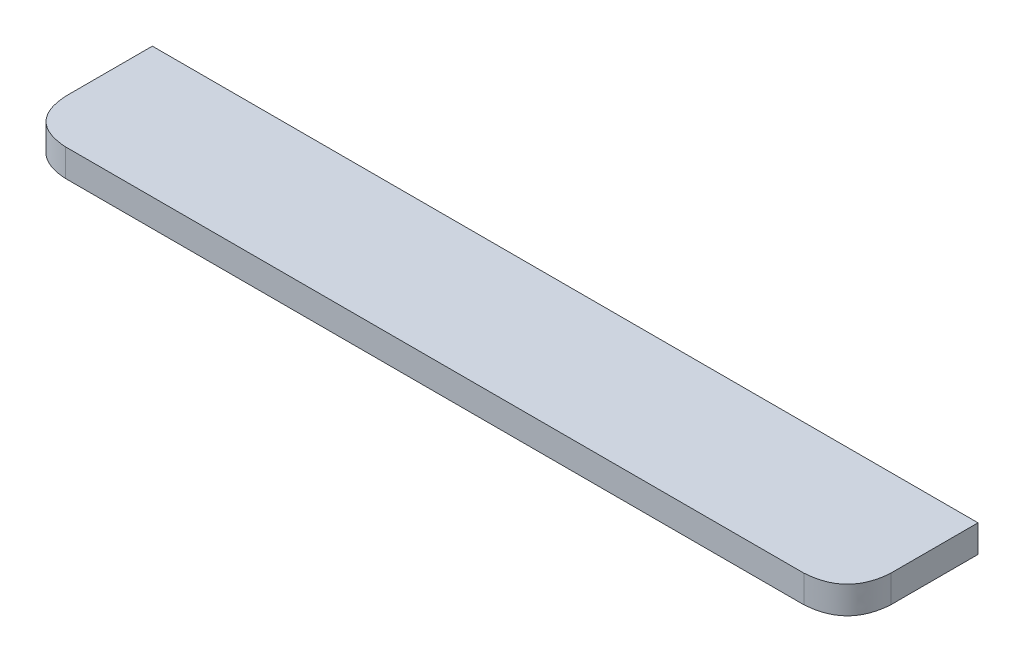
SolidWorks part; units mm, degrees
ref_plane "Front Plane" through (0, 0, 0) normal (0, 0, 1) x (1, 0, 0)
ref_plane "Top Plane" through (0, 0, 0) normal (0, 1, 0) x (1, 0, 0)
ref_plane "Right Plane" through (0, 0, 0) normal (1, 0, 0) x (0, 0, -1)
sketch "Sketch2" plane through (0, 0, 0) normal (0, 1, 0) x (1, 0, 0)
  line L0 (0, 0) -> (0, -25.4) construction
  line L1 (-107.696, -25.4) -> (107.696, -25.4)
  line L5 (0, 0) -> (0, 12.7) construction
  line L6 (120.396, 12.7) -> (-120.396, 12.7)
  line L7 (107.696, -25.4) -> (107.696, -12.7) construction
  line L8 (107.696, -12.7) -> (116.8559, -21.8599) construction
  line L9 (107.696, -12.7) -> (120.396, -12.7) construction
  line L11 (-107.696, -12.7) -> (-120.396, -12.7) construction
  line L13 (-107.696, -12.7) -> (-116.8559, -21.8599) construction
  line L14 (-107.696, -25.4) -> (-107.696, -12.7) construction
  line L15 (120.396, 12.7) -> (120.396, -12.7)
  line L16 (-120.396, 12.7) -> (-120.396, -12.7)
  spline S0 degree 2 poles (107.696, -25.4) (119.6657, -24.6697) (120.396, -12.7) knots 0 0 0 1 1 1
  spline S1 degree 2 poles (-107.696, -25.4) (-119.6657, -24.6697) (-120.396, -12.7) knots 0 0 0 1 1 1
  point P0 (0, 0)
  dimension "D2" = 25.4
extrude "Boss-Extrude1" add sketch "Sketch2" along normal blind 8
